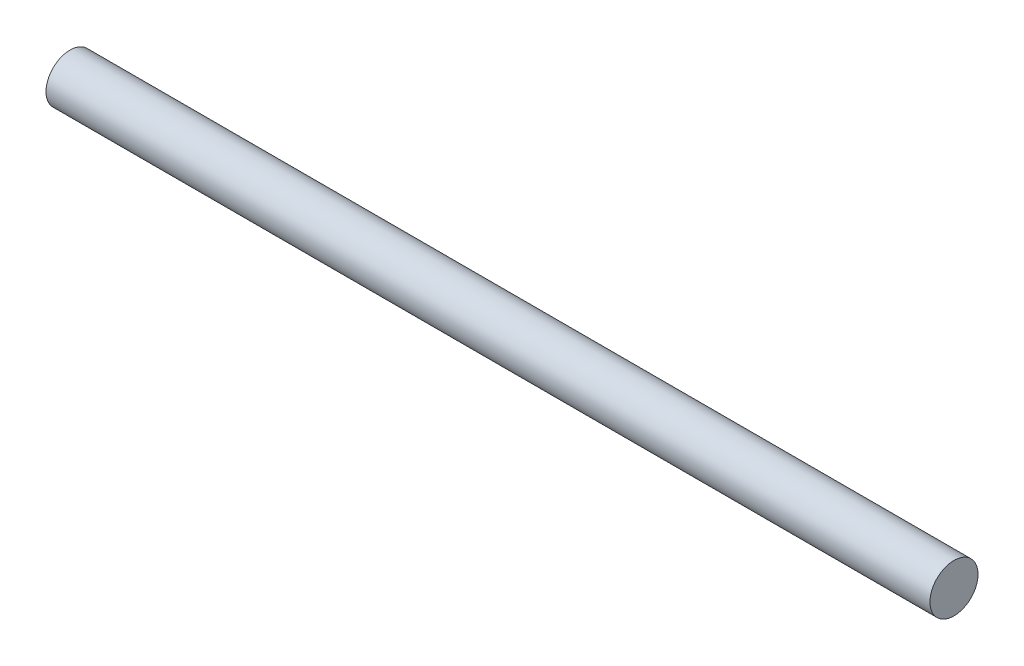
SolidWorks part; units mm, degrees
ref_plane "Front Plane" through (0, 0, 0) normal (0, 0, 1) x (1, 0, 0)
ref_plane "Top Plane" through (0, 0, 0) normal (0, 1, 0) x (1, 0, 0)
ref_plane "Right Plane" through (0, 0, 0) normal (1, 0, 0) x (0, 0, -1)
sketch "Sketch1" plane through (0, 0, 0) normal (1, 0, 0) x (0, 0, -1)
  circle A0 centre (0, 0) radius 3.1
extrude "Boss-Extrude1" add sketch "Sketch1" along normal blind 114
